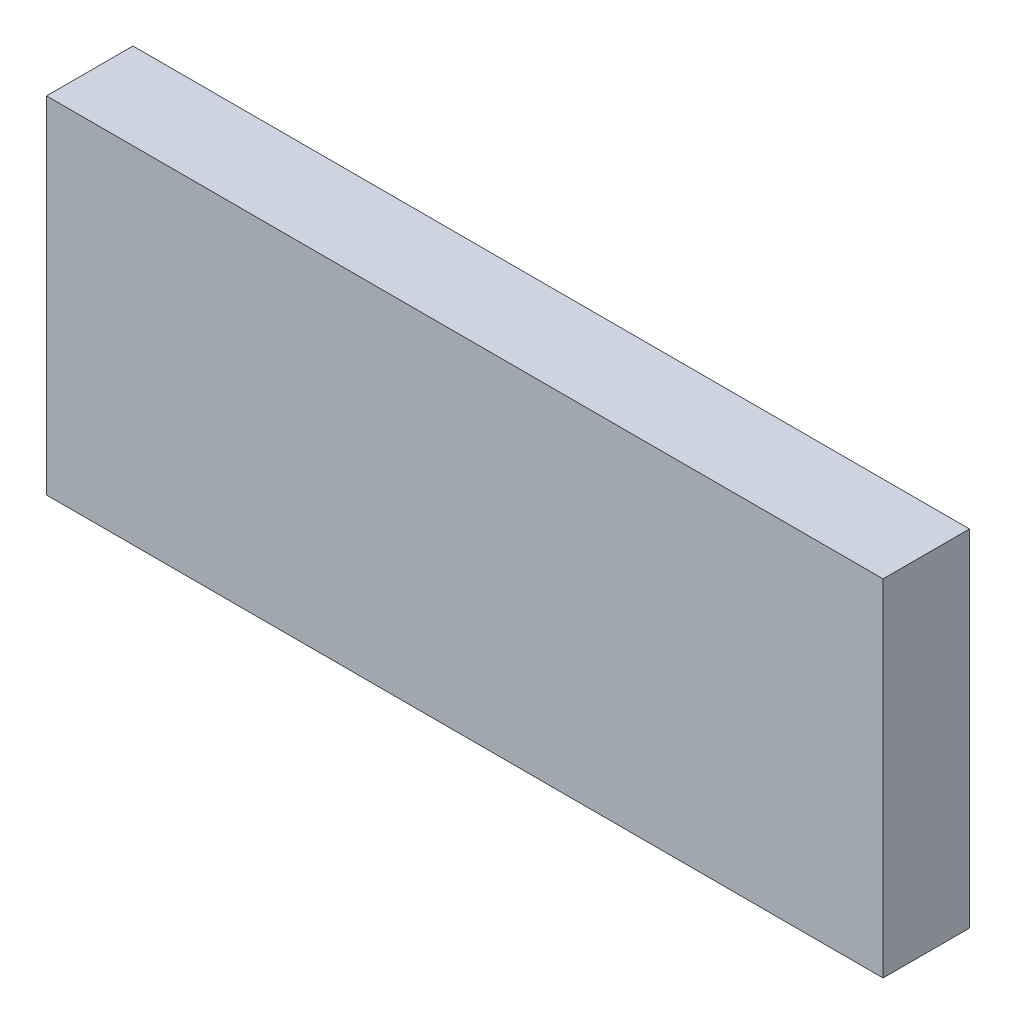
SolidWorks part; units mm, degrees
ref_plane "Alzado" through (0, 0, 0) normal (0, 0, 1) x (1, 0, 0)
ref_plane "Planta" through (0, 0, 0) normal (0, 1, 0) x (1, 0, 0)
ref_plane "Vista lateral" through (0, 0, 0) normal (1, 0, 0) x (0, 0, -1)
sketch "Croquis1" plane through (0, 0, 0) normal (0, 0, 1) x (1, 0, 0)
  line L1 (-48.4025, -20) -> (48.4025, -20)
  line L2 (-48.4025, -20) -> (-48.4025, 20)
  line L3 (-48.4025, 20) -> (48.4025, 20)
  line L4 (48.4025, -20) -> (48.4025, 20)
  line L5 (-48.4025, -20) -> (48.4025, 20) construction
  line L6 (-48.4025, 20) -> (48.4025, -20) construction
  point P0 (0, 0)
  dimension "D1" = 40
extrude "Saliente-Extruir1" add sketch "Croquis1" along normal blind 10
